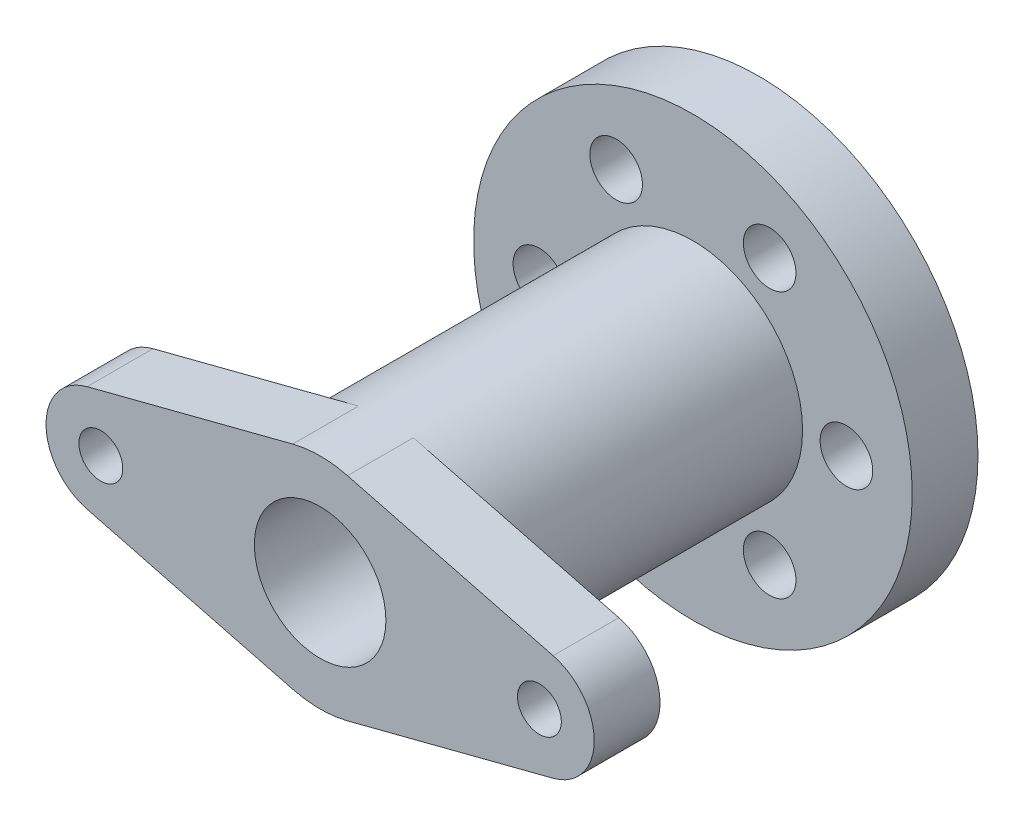
SolidWorks part; units mm, degrees
ref_plane "Front Plane" through (0, 0, 0) normal (0, 0, 1) x (1, 0, 0)
ref_plane "Top Plane" through (0, 0, 0) normal (0, 1, 0) x (1, 0, 0)
ref_plane "Right Plane" through (0, 0, 0) normal (1, 0, 0) x (0, 0, -1)
sketch "Sketch1" plane through (0, 0, 0) normal (1, 0, 0) x (0, 0, -1)
  line L0 (0, 0) -> (85, 0) construction
  line L1 (85, 0) -> (85, 50)
  line L2 (85, 50) -> (70, 50)
  line L3 (70, 50) -> (70, 25)
  line L4 (70, 25) -> (0, 25)
  line L5 (0, 25) -> (0, 0)
  line L6 (0, 0) -> (85, 0)
  point P3 (74.2809, 50)
  dimension "D1" = 100
  dimension "D2" = 50
  dimension "D3" = 85
  dimension "D4" = 15
revolve "Revolve1" add sketch "Sketch1" angle 360 about L0
sketch "Sketch2" plane through (0, 0, 0) normal (0, 0, 1) x (1, 0, 0)
  line L0 (0, 0) -> (-50, 0) construction
  line L1 (-6.25, 24.2061) -> (-53.125, 12.1031)
  line L2 (0, 0) -> (0, 25) construction
  line L3 (-6.25, -24.2061) -> (-53.125, -12.1031)
  line L4 (6.25, -24.2061) -> (53.125, -12.1031)
  line L5 (6.25, 24.2061) -> (53.125, 12.1031)
  circle A1 centre (0, 0) radius 25
  arc A2 (-6.25, -24.2061) -> (6.25, -24.2061) centre (0, 0) ccw
  circle A3 centre (-50, 0) radius 5
  circle A4 centre (0, 0) radius 50 construction
  circle A5 centre (50, 0) radius 5
  arc A6 (-53.125, 12.1031) -> (-53.125, -12.1031) centre (-50, 0) ccw
  arc A7 (53.125, -12.1031) -> (53.125, 12.1031) centre (50, 0) ccw
  arc A8 (6.25, 24.2061) -> (-6.25, 24.2061) centre (0, 0) ccw
  point P13 (-57.9006, 21.111)
  point P15 (0, 0)
  point P16 (0, 0)
  dimension "D2" = 10
  dimension "D3" = 25
  dimension "D1" = 0
extrude "Boss-Extrude1" add sketch "Sketch2" along normal blind 15
sketch "Sketch3" plane through (0, 0, 15) normal (0, 0, 1) x (1, 0, 0)
  circle A0 centre (0, 0) radius 15
  dimension "D1" = 30
extrude "Cut-Extrude1" cut sketch "Sketch3" against normal up to surface (100 mm away) up to face at (50, 0, -85)
hole_wizard "Ø12.0mm Dowel Hole1" positions "Sketch4" profile "Sketch5" hole size "Ø12.0" standard "ANSI Metric"
sketch "Sketch4" plane through (0, 0, -85) normal (0, 0, -1) x (-1, 0, 0)
  circle A0 centre (0, 0) radius 35 construction
  point P5 (-35, 0)
  point P17 (-17.5, 30.3109)
  point P18 (17.5, 30.3109)
  point P19 (35, 0)
  point P20 (17.5, -30.3109)
  point P21 (-17.5, -30.3109)
  point P23 (0, 0)
  point P24 (0, 0)
  dimension "D1" = 70
  dimension "D2" = 6
sketch "Sketch5" plane through (17.5, -30.3109, -85) normal (1, 0, 0) x (0, 1, 0)
  line L0 (0, 0) -> (0, 18.6042)
  line L1 (0, 18.6042) -> (6, 14.999)
  line L2 (6, 14.999) -> (6, 0)
  line L5 (6, 0) -> (0, 0)
  line L10 (0, 18.6042) -> (-6, 14.999) construction
  line L11 (0, -6.35) -> (0, 107.95) construction
  dimension "Hole Dia." = 12
  dimension "Hole Depth" = 14.999
  dimension "Drill Angle" = 118
